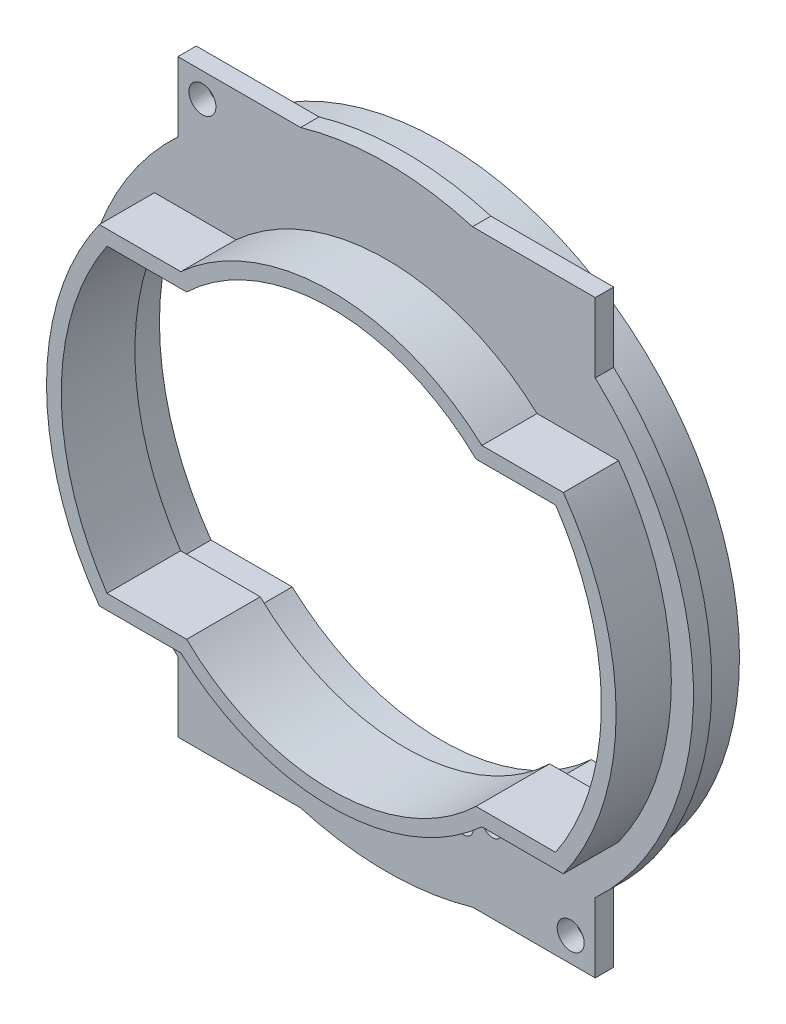
SolidWorks part; units mm, degrees
ref_plane "前视基准面" through (0, 0, 0) normal (0, 0, 1) x (1, 0, 0)
ref_plane "上视基准面" through (0, 0, 0) normal (0, 1, 0) x (1, 0, 0)
ref_plane "右视基准面" through (0, 0, 0) normal (1, 0, 0) x (0, 0, -1)
other "Configuration Table"
sketch "草图1" plane through (0, 0, 0) normal (0, 0, 1) x (1, 0, 0)
  line L0 (18.274, 12.25) -> (-18.274, 12.25)
  line L1 (-18.274, -12.25) -> (18.274, -12.25)
  line L2 (-26.9084, 0) -> (29.3247, 0) construction
  circle A0 centre (0, 0) radius 17
  circle A1 centre (0, 0) radius 22
  circle A2 centre (0, 0) radius 25
  dimension "D1" = 34
  dimension "D2" = 44
  dimension "D4" = 50
  dimension "D3" = 24.5
extrude "凸台-拉伸1" add sketch "草图1" along normal blind 1.5 contours A2 L2 A1 | L2 A2 A1 | L1 A1 A0 | L0 A1 A0
sketch "草图2" plane through (0, 0, 1.5) normal (0, 0, 1) x (1, 0, 0)
  line L0 (-18.274, 12.25) -> (-11.7872, 12.25)
  line L1 (11.7872, 12.25) -> (18.274, 12.25)
  line L2 (11.7872, -12.25) -> (18.274, -12.25)
  line L3 (-18.274, -12.25) -> (-11.7872, -12.25)
  line L4 (-18.9034, 13.45) -> (-12.2612, 13.45)
  line L5 (12.2612, 13.45) -> (18.9034, 13.45)
  line L6 (12.2612, -13.45) -> (18.9034, -13.45)
  line L7 (-18.9034, -13.45) -> (-12.2612, -13.45)
  arc A0 (18.274, 12.25) -> (18.274, -12.25) centre (0, 0) cw
  arc A1 (11.7872, -12.25) -> (-11.7872, -12.25) centre (0, 0) cw
  arc A2 (-11.7872, 12.25) -> (11.7872, 12.25) centre (0, 0) cw
  arc A3 (-18.274, -12.25) -> (-18.274, 12.25) centre (0, 0) cw
  arc A4 (-12.2612, 13.45) -> (12.2612, 13.45) centre (0, 0) cw
  arc A5 (18.9034, 13.45) -> (18.9034, -13.45) centre (0, 0) cw
  arc A6 (12.2612, -13.45) -> (-12.2612, -13.45) centre (0, 0) cw
  arc A7 (-18.9034, -13.45) -> (-18.9034, 13.45) centre (0, 0) cw
  dimension "D1" = 1.2
extrude "凸台-拉伸2" add sketch "草图2" along normal blind 4.5
sketch "草图5" plane through (0, 0, 0) normal (0, 0, -1) x (-1, 0, 0)
  line L40 (-18.7999, -13.25) -> (-12.1835, -13.25)
  line L41 (12.1835, -13.25) -> (18.7999, -13.25)
  line L42 (18.7999, 13.25) -> (12.1835, 13.25)
  line L43 (-12.1835, 13.25) -> (-18.7999, 13.25)
  line L44 (-18.7999, -13.25) -> (-12.1835, -13.25)
  line L45 (12.1835, -13.25) -> (18.7999, -13.25)
  line L46 (18.7999, 13.25) -> (12.1835, 13.25)
  line L47 (-12.1835, 13.25) -> (-18.7999, 13.25)
  circle A37 centre (0, 0) radius 24.25
  arc A41 (-18.7999, 13.25) -> (-18.7999, -13.25) centre (0, 0) ccw
  arc A42 (-12.1835, -13.25) -> (12.1835, -13.25) centre (0, 0) ccw
  arc A43 (18.7999, -13.25) -> (18.7999, 13.25) centre (0, 0) ccw
  arc A44 (12.1835, 13.25) -> (-12.1835, 13.25) centre (0, 0) ccw
  arc A45 (-18.7999, 13.25) -> (-18.7999, -13.25) centre (0, 0) ccw
  arc A46 (-12.1835, -13.25) -> (12.1835, -13.25) centre (0, 0) ccw
  arc A47 (18.7999, -13.25) -> (18.7999, 13.25) centre (0, 0) ccw
  arc A48 (12.1835, 13.25) -> (-12.1835, 13.25) centre (0, 0) ccw
  dimension "D2" = 48.5
  dimension "D1" = 1
extrude "凸台-拉伸4" add sketch "草图5" along normal blind 3
sketch "草图6" plane through (0, 0, 0) normal (0, 0, 1) x (1, 0, 0)
  line L1 (-17, -24) -> (17, -24)
  line L2 (-17, -24) -> (-17, 24)
  line L3 (-17, 24) -> (17, 24)
  line L4 (17, -24) -> (17, 24)
  line L5 (-17, -24) -> (17, 24) construction
  line L6 (-17, 24) -> (17, -24) construction
  circle A2 centre (0, 0) radius 24
  point P0 (0, 0)
  dimension "D1" = 34
  dimension "D2" = 48
extrude "凸台-拉伸5" add sketch "草图6" along normal blind 1.5 contours A2 L3 L2 | A2 L4 L3 | A2 L1 L4 | A2 L2 L1
sketch "草图7" plane through (0, 0, -3) normal (0, 0, -1) x (-1, 0, 0)
  line L0 (-12.8572, -14.6609) -> (0, 0) construction
  line L1 (0, 0) -> (0, -19.5) construction
  line L2 (0, 0) -> (-12.8572, -14.6609) construction
  line L3 (0, 0) -> (-10.8336, -16.2137) construction
  circle A0 centre (0, 0) radius 19.5 construction
  circle A1 centre (-12.8572, -14.6609) radius 0.5
  circle A2 centre (-10.8336, -16.2137) radius 0.5
  circle A3 centre (-8.6246, -17.489) radius 0.5
  circle A4 centre (-6.2681, -18.4651) radius 0.5
  circle A5 centre (-3.8043, -19.1253) radius 0.5
  circle A6 centre (-1.2754, -19.4582) radius 0.5
  circle A7 centre (1.2754, -19.4582) radius 0.5
  circle A8 centre (3.8043, -19.1253) radius 0.5
  circle A9 centre (6.2681, -18.4651) radius 0.5
  circle A10 centre (8.6246, -17.489) radius 0.5
  dimension "D1" = 39
  dimension "D2" = 1
  dimension "D3" = 41.25
  dimension "D5" = 7.5
  dimension "D4" = 10
extrude "切除-拉伸2" cut sketch "草图7" against normal through all
sketch "草图8" plane through (0, 0, 1.5) normal (0, 0, 1) x (1, 0, 0)
  line L0 (0, 0) -> (12.8572, -14.6609) construction
  line L1 (0, 0) -> (10.8336, -16.2137) construction
  circle A0 centre (12.8572, -14.6609) radius 0.8
  circle A1 centre (10.8336, -16.2137) radius 0.8
  circle A2 centre (8.6246, -17.489) radius 0.8
  circle A3 centre (6.2681, -18.4651) radius 0.8
  circle A4 centre (3.8043, -19.1253) radius 0.8
  circle A5 centre (1.2754, -19.4582) radius 0.8
  circle A6 centre (-1.2754, -19.4582) radius 0.8
  circle A7 centre (-3.8043, -19.1253) radius 0.8
  circle A8 centre (-6.2681, -18.4651) radius 0.8
  circle A9 centre (-8.6246, -17.489) radius 0.8
  dimension "D1" = 1.6
  dimension "D3" = 7.5
  dimension "D2" = 10
extrude "切除-拉伸3" cut sketch "草图8" against normal blind 4
sketch "草图9" plane through (0, 0, 1.5) normal (0, 0, 1) x (1, 0, 0)
  line L0 (-17, 24) -> (-7, 24) construction
  line L1 (-17, 18.3303) -> (-17, 24) construction
  line L2 (17, -24) -> (17, -18.3303) construction
  line L3 (7, -24) -> (17, -24) construction
  circle A0 centre (-15, 22) radius 1.1
  circle A1 centre (15, -22) radius 1.1
  dimension "D1" = 2.2
  dimension "D2" = 2
  dimension "D3" = 2
  dimension "D4" = 2
  dimension "D5" = 2
extrude "切除-拉伸4" cut sketch "草图9" against normal blind 10
